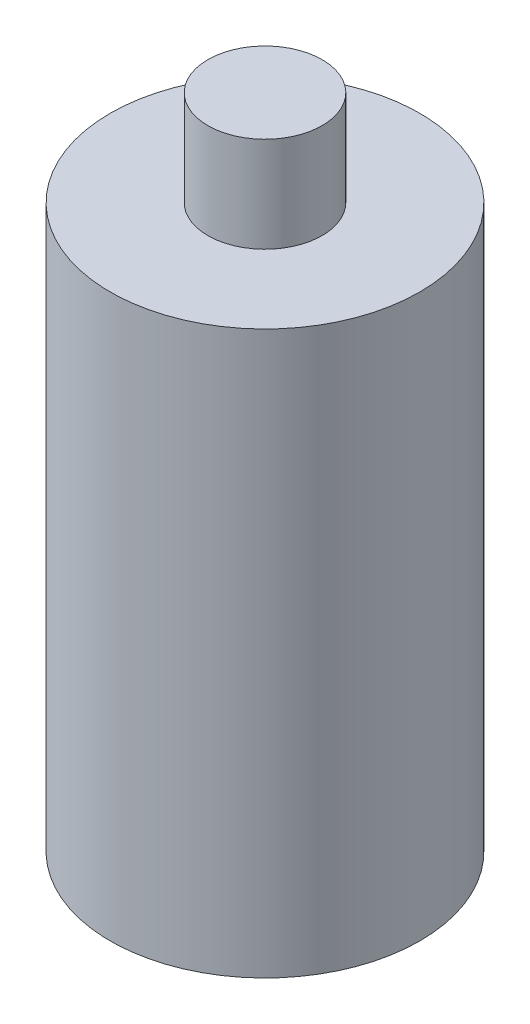
SolidWorks part; units mm, degrees
ref_plane "Front Plane" through (0, 0, 0) normal (0, 0, 1) x (1, 0, 0)
ref_plane "Top Plane" through (0, 0, 0) normal (0, 1, 0) x (1, 0, 0)
ref_plane "Right Plane" through (0, 0, 0) normal (1, 0, 0) x (0, 0, -1)
sketch "Sketch1" plane through (0, 0, 0) normal (0, 0, 1) x (1, 0, 0)
  line L0 (0, 0) -> (3.25, 0)
  line L1 (3.25, 0) -> (3.25, 11.8)
  line L2 (3.25, 11.8) -> (1.2, 11.8)
  line L3 (1.2, 11.8) -> (1.2, 13.8)
  line L4 (1.2, 13.8) -> (0, 13.8)
  line L5 (0, 13.8) -> (0, 0)
  dimension "D1" = 3.25
  dimension "D2" = 1.2
  dimension "D3" = 2
  dimension "D4" = 11.8
revolve "Revolve1" add sketch "Sketch1" angle 360 about L5
